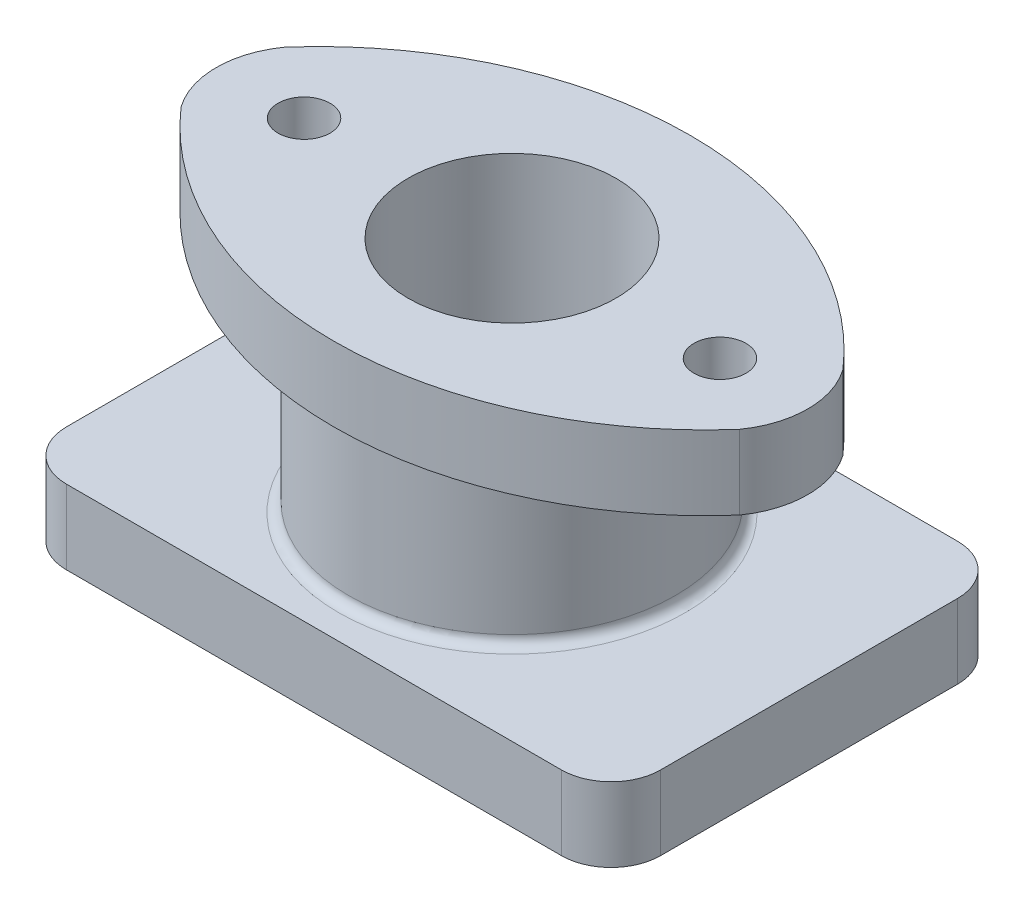
SolidWorks part; units mm, degrees
material "Gray Cast Iron"
ref_plane "Front Plane" through (0, 0, 0) normal (0, 0, 1) x (1, 0, 0)
ref_plane "Top Plane" through (0, 0, 0) normal (0, 1, 0) x (1, 0, 0)
ref_plane "Right Plane" through (0, 0, 0) normal (1, 0, 0) x (0, 0, -1)
sketch "Sketch1" plane through (0, 0, 0) normal (0, 1, 0) x (1, 0, 0)
  line L1 (-60, 40) -> (60, 40)
  line L2 (-60, 40) -> (-60, -40)
  line L3 (-60, -40) -> (60, -40)
  line L4 (60, 40) -> (60, -40)
  line L5 (-60, 40) -> (60, -40) construction
  line L6 (-60, -40) -> (60, 40) construction
  point P0 (0, 0)
  dimension "D1" = 80
  dimension "D2" = 120
extrude "Boss-Extrude1" add sketch "Sketch1" along normal blind 15
sketch "Sketch2" plane through (0, 0, 0) normal (0, 1, 0) x (1, 0, 0)
  circle A0 centre (0, 0) radius 33
  dimension "D1" = 66
extrude "Boss-Extrude2" add sketch "Sketch2" along normal blind 48
sketch "Sketch3" plane through (0, 48, 0) normal (0, 1, 0) x (1, 0, 0)
  line L0 (0, 0) -> (0, 40) construction
  line L1 (60, 40) -> (-60, 40) construction
  line L2 (0, 0) -> (-60, 0) construction
  line L3 (-60, 40) -> (-60, -40) construction
  arc A0 (-56.391, 10.4474) -> (56.391, 10.4474) centre (0, -39) cw
  arc A1 (-56.391, -10.4474) -> (56.391, -10.4474) centre (0, 39) ccw
  arc A2 (-56.391, -10.4474) -> (-56.391, 10.4474) centre (-41.7333, 0) cw
  arc A3 (56.391, -10.4474) -> (56.391, 10.4474) centre (41.7333, 0) ccw
  point P19 (0, -36)
  point P20 (0, 36)
  dimension "D1" = 75
  dimension "D2" = 72
  dimension "D3" = 18
extrude "Boss-Extrude3" add sketch "Sketch3" along normal blind 15
sketch "Sketch10" plane through (0, 63, 0) normal (0, 1, 0) x (1, 0, 0)
  circle A0 centre (0, 0) radius 21
  dimension "D1" = 42
extrude "Cut-Extrude1" cut sketch "Sketch10" against normal blind 48
sketch "Sketch11" plane through (0, 15, 0) normal (0, 1, 0) x (1, 0, 0)
  circle A0 centre (0, 0) radius 16.5
  dimension "D1" = 33
extrude "Cut-Extrude2" cut sketch "Sketch11" against normal blind 15
sketch "Sketch12" plane through (0, 63, 0) normal (0, 1, 0) x (1, 0, 0)
  line L0 (0, 0) -> (0, 36) construction
  arc A0 (56.391, 10.4474) -> (-56.391, 10.4474) centre (0, -39) ccw construction
  point P0 (-42, 0)
  point P8 (42, 0)
  dimension "D1" = 42
hole_wizard "M12x1.5 Tapped Hole1" positions "3DSketch5" profile "Sketch13" tap size "M12x1.5" standard "ISO"
sketch3d "3DSketch5"
  point P0 (-42, 63, 0)
  point P3 (42, 63, 0)
sketch "Sketch13" plane through (-42, 63, 0) normal (1, 0, 0) x (0, 0, 1)
  line L0 (0, 0) -> (0, 15)
  line L1 (0, 15) -> (5.25, 15)
  line L2 (5.25, 15) -> (5.25, 0)
  line L5 (5.25, 0) -> (0, 0)
  line L11 (0, -6.35) -> (0, 107.95) construction
  dimension "Thru Tap Drill Dia." = 10.5
  dimension "Thru Tap Drill Depth" = 15
cosmetic thread "Hole Thread1" parameters "D2"=12
cosmetic thread "Hole Thread2" parameters "D2"=12
fillet "Fillet2" radius 2 2 edges at (0, 15, 33) (0, 48, 33)
fillet "Fillet3" radius 10 4 edges at (-60, 7.5, -40) (60, 7.5, -40) (60, 7.5, 40) (-60, 7.5, 40)
